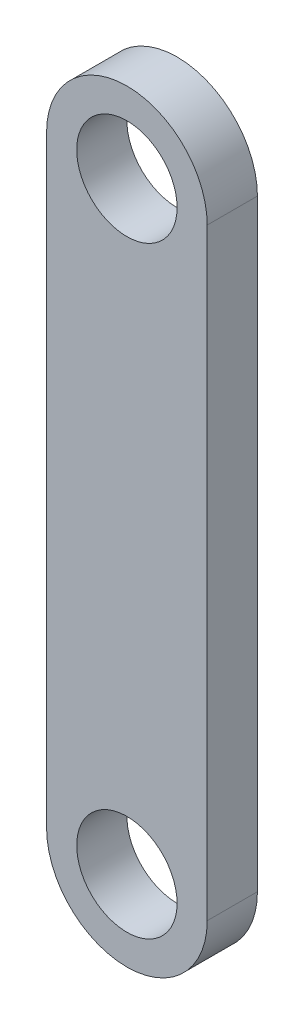
SolidWorks part; units mm, degrees
ref_plane "前基準面" through (0, 0, 0) normal (0, 0, 1) x (1, 0, 0)
ref_plane "上基準面" through (0, 0, 0) normal (0, 1, 0) x (1, 0, 0)
ref_plane "右基準面" through (0, 0, 0) normal (1, 0, 0) x (0, 0, -1)
sketch "草圖1" plane through (0, 0, 0) normal (0, 0, 1) x (1, 0, 0)
  line L0 (0, -3) -> (0, 3) construction
  line L1 (-0.8, -3) -> (-0.8, 3)
  line L2 (0.8, -3) -> (0.8, 3)
  arc A0 (-0.8, -3) -> (0.8, -3) centre (0, -3) ccw
  arc A1 (0.8, 3) -> (-0.8, 3) centre (0, 3) ccw
  circle A2 centre (0, 3) radius 0.5
  circle A3 centre (0, -3) radius 0.5
  point P2 (0, 0)
  dimension "D1" = 1
  dimension "D2" = 0.8
  dimension "D4" = 1
  dimension "D3" = 6
extrude "填料-伸長1" add sketch "草圖1" along normal blind 0.5
